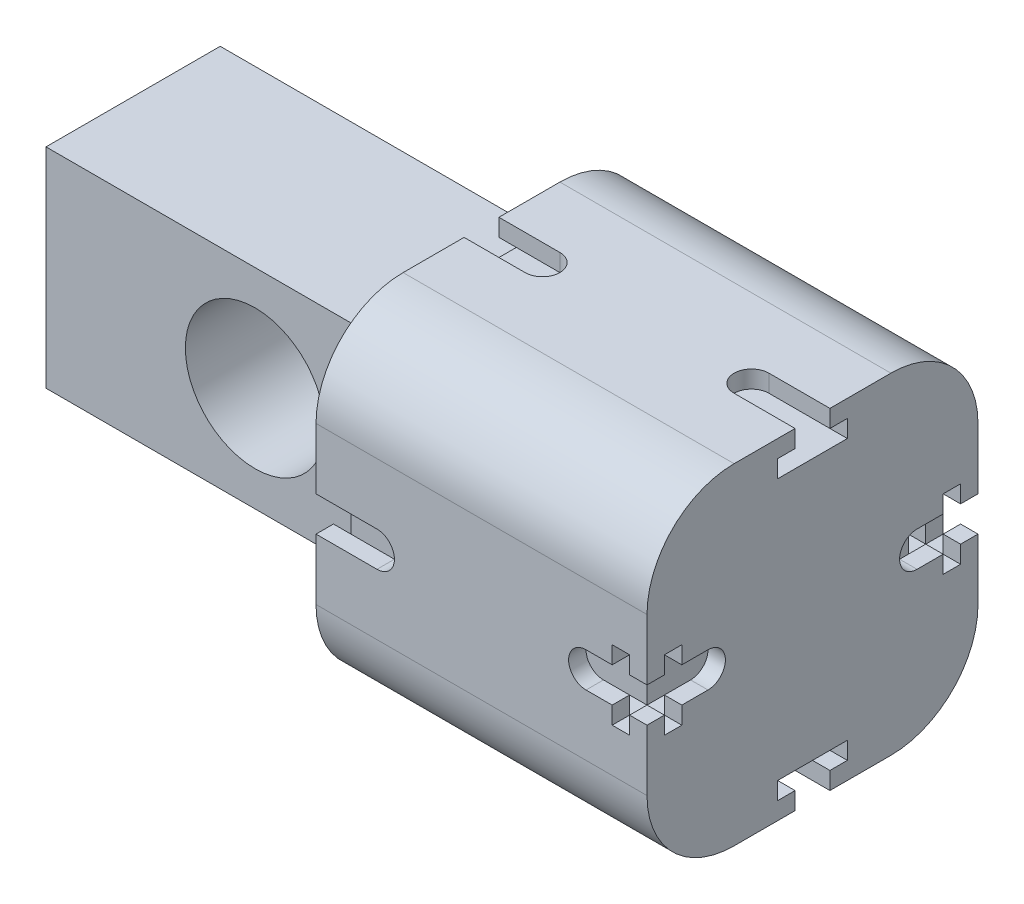
SolidWorks part; units mm, degrees
ref_plane "前视基准面" through (0, 0, 0) normal (0, 0, 1) x (1, 0, 0)
ref_plane "上视基准面" through (0, 0, 0) normal (0, 1, 0) x (1, 0, 0)
ref_plane "右视基准面" through (0, 0, 0) normal (1, 0, 0) x (0, 0, -1)
sketch "草图2" plane through (0, 0, 0) normal (0, 0, 1) x (1, 0, 0)
  line L1 (-9.5, 9.5) -> (9.5, 9.5)
  line L2 (-9.5, 9.5) -> (-9.5, -9.5)
  line L3 (-9.5, -9.5) -> (9.5, -9.5)
  line L4 (9.5, 9.5) -> (9.5, -9.5)
  line L5 (-9.5, 9.5) -> (9.5, -9.5) construction
  line L6 (-9.5, -9.5) -> (9.5, 9.5) construction
  point P0 (0, 0)
extrude "凸台-拉伸1" add sketch "草图2" along normal mid plane 19
fillet "圆角1" radius 5 1 edges at (0, 9.5, 9.5)
fillet "圆角2" radius 5 3 edges at (0, -9.5, 9.5) (0, 9.5, -9.5) (0, -9.5, -9.5)
ref_plane "基准面1" through (0, -7.5, 0) normal (0, -1, 0) x (-1, 0, 0)
sketch "草图7" plane through (0, -7.5, 0) normal (0, -1, 0) x (-1, 0, 0)
  line L0 (9.5, -4.5) -> (9.5, 4.5) construction
  line L1 (-9.5, 2) -> (-4, 2)
  line L2 (-9.5, 2) -> (-9.5, -2)
  line L3 (-9.5, -2) -> (-4, -2)
  line L4 (9.5, 2) -> (9.5, -2)
  line L5 (4, 2) -> (9.5, 2)
  line L6 (4, -2) -> (9.5, -2)
  line L9 (-4, 2) -> (-4, -2)
  line L11 (4, 2) -> (4, -2)
  point P0 (0, 0)
  point P8 (0, 0)
sketch "草图9" plane through (0, -9.5, 0) normal (0, -1, 0) x (1, 0, 0)
  line L0 (6, 1) -> (9.5, 1)
  line L1 (9.5, 1) -> (9.5, -1)
  line L2 (9.5, -1) -> (6, -1)
  line L4 (-9.5, 1) -> (-9.5, -1)
  line L5 (-6, 1) -> (-9.5, 1)
  line L6 (-9.5, -1) -> (-6, -1)
  arc A0 (6, 1) -> (6, -1) centre (6, 0) ccw
  arc A1 (-6, 1) -> (-6, -1) centre (-6, 0) cw
extrude "切除-拉伸5" cut sketch "草图7" along normal blind 1
extrude "切除-拉伸6" cut sketch "草图9" against normal blind 1
ref_plane "基准面2" through (0, 0, 7.5) normal (0, 0, 1) x (1, 0, 0)
ref_plane "基准面3" through (0, 7.5, 0) normal (0, 1, 0) x (1, 0, 0)
ref_plane "基准面4" through (0, 0, -7.5) normal (0, 0, -1) x (-1, 0, 0)
sketch "草图13" plane through (0, 0, 7.5) normal (0, 0, 1) x (1, 0, 0)
  line L1 (-9.5, 2) -> (-4, 2)
  line L2 (-9.5, 2) -> (-9.5, -2)
  line L3 (-9.5, -2) -> (-4, -2)
  line L4 (9.5, 2) -> (9.5, -2)
  line L5 (4, 2) -> (9.5, 2)
  line L6 (4, -2) -> (9.5, -2)
  line L9 (-4, 2) -> (-4, -2)
  line L11 (4, 2) -> (4, -2)
  point P0 (0, 0)
  point P8 (0, 0)
sketch "草图14" plane through (0, 7.5, 0) normal (0, 1, 0) x (1, 0, 0)
  line L1 (-9.5, 2) -> (-4, 2)
  line L2 (-9.5, 2) -> (-9.5, -2)
  line L3 (-9.5, -2) -> (-4, -2)
  line L4 (9.5, 2) -> (9.5, -2)
  line L5 (4, 2) -> (9.5, 2)
  line L6 (4, -2) -> (9.5, -2)
  line L9 (-4, 2) -> (-4, -2)
  line L11 (4, 2) -> (4, -2)
  point P0 (0, 0)
  point P8 (0, 0)
sketch "草图15" plane through (0, 0, -7.5) normal (0, 0, -1) x (-1, 0, 0)
  line L1 (-9.5, 2) -> (-4, 2)
  line L2 (-9.5, 2) -> (-9.5, -2)
  line L3 (-9.5, -2) -> (-4, -2)
  line L4 (9.5, 2) -> (9.5, -2)
  line L5 (4, 2) -> (9.5, 2)
  line L6 (4, -2) -> (9.5, -2)
  line L9 (-4, 2) -> (-4, -2)
  line L11 (4, 2) -> (4, -2)
  point P0 (0, 0)
  point P8 (0, 0)
extrude "切除-拉伸10" cut sketch "草图13" along normal blind 1
extrude "切除-拉伸11" cut sketch "草图14" along normal blind 1
extrude "切除-拉伸12" cut sketch "草图15" along normal blind 1
sketch "草图20" plane through (0, 0, 7.5) normal (0, 0, 1) x (-1, 0, 0)
  line L0 (6, 1) -> (9.5, 1)
  line L1 (9.5, 1) -> (9.5, -1)
  line L2 (9.5, -1) -> (6, -1)
  line L4 (-9.5, 1) -> (-9.5, -1)
  line L5 (-6, 1) -> (-9.5, 1)
  line L6 (-9.5, -1) -> (-6, -1)
  arc A0 (6, 1) -> (6, -1) centre (6, 0) ccw
  arc A1 (-6, 1) -> (-6, -1) centre (-6, 0) cw
sketch "草图21" plane through (0, 7.5, 0) normal (0, 1, 0) x (-1, 0, 0)
  line L0 (6, 1) -> (9.5, 1)
  line L1 (9.5, 1) -> (9.5, -1)
  line L2 (9.5, -1) -> (6, -1)
  line L4 (-9.5, 1) -> (-9.5, -1)
  line L5 (-6, 1) -> (-9.5, 1)
  line L6 (-9.5, -1) -> (-6, -1)
  arc A0 (6, 1) -> (6, -1) centre (6, 0) ccw
  arc A1 (-6, 1) -> (-6, -1) centre (-6, 0) cw
sketch "草图22" plane through (0, 0, -7.5) normal (0, 0, -1) x (1, 0, 0)
  line L0 (6, 1) -> (9.5, 1)
  line L1 (9.5, 1) -> (9.5, -1)
  line L2 (9.5, -1) -> (6, -1)
  line L4 (-9.5, 1) -> (-9.5, -1)
  line L5 (-6, 1) -> (-9.5, 1)
  line L6 (-9.5, -1) -> (-6, -1)
  arc A0 (6, 1) -> (6, -1) centre (6, 0) ccw
  arc A1 (-6, 1) -> (-6, -1) centre (-6, 0) cw
extrude "切除-拉伸13" cut sketch "草图20" along normal blind 2
extrude "切除-拉伸14" cut sketch "草图21" along normal blind 2
extrude "切除-拉伸15" cut sketch "草图22" along normal blind 2
ref_plane "基准面5" through (7.5, 0, 0) normal (1, 0, 0) x (0, 0, -1)
sketch "草图23" plane through (7.5, 0, 0) normal (1, 0, 0) x (0, 0, -1)
  line L1 (-9.5, 2) -> (-4, 2)
  line L2 (-9.5, 2) -> (-9.5, -2)
  line L3 (-9.5, -2) -> (-4, -2)
  line L4 (9.5, 2) -> (9.5, -2)
  line L5 (4, 2) -> (9.5, 2)
  line L6 (4, -2) -> (9.5, -2)
  line L9 (-4, 2) -> (-4, -2)
  line L11 (4, 2) -> (4, -2)
  point P0 (0, 0)
  point P8 (0, 0)
extrude "切除-拉伸16" cut sketch "草图23" along normal blind 1
sketch "草图24" plane through (7.5, 0, 0) normal (1, 0, 0) x (0, 0, 1)
  line L0 (6, 1) -> (9.5, 1)
  line L1 (9.5, 1) -> (9.5, -1)
  line L2 (9.5, -1) -> (6, -1)
  line L4 (-9.5, 1) -> (-9.5, -1)
  line L5 (-6, 1) -> (-9.5, 1)
  line L6 (-9.5, -1) -> (-6, -1)
  arc A0 (6, 1) -> (6, -1) centre (6, 0) ccw
  arc A1 (-6, 1) -> (-6, -1) centre (-6, 0) cw
extrude "切除-拉伸17" cut sketch "草图24" along normal blind 2
ref_plane "基准面6" through (-7.5, 0, 0) normal (-1, 0, 0) x (0, 0, 1)
sketch "草图27" plane through (-9.5, 0, 0) normal (-1, 0, 0) x (0, 0, 1)
  line L5 (-5, 6) -> (5, 6)
  line L6 (-5, 6) -> (-5, -6)
  line L7 (-5, -6) -> (5, -6)
  line L8 (5, 6) -> (5, -6)
  line L9 (-5, 6) -> (5, -6) construction
  line L10 (-5, -6) -> (5, 6) construction
  point P0 (0, 0)
  point P1 (0, 0)
  dimension "D1" = 12
  dimension "D2" = 10
extrude "凸台-拉伸2" add sketch "草图27" along normal blind 20
sketch "草图28" plane through (0, 0, 0) normal (0, 0, 1) x (1, 0, 0)
  line L0 (-9.5, 4.5) -> (-9.5, 1) construction
  circle A0 centre (-17.5, 0) radius 4
  dimension "D1" = 8
extrude "切除-拉伸20" cut sketch "草图28" against normal mid plane 20
sketch "草图11" plane through (0, 7.5, 0) normal (0, 1, 0) x (-1, 0, 0)
  line L0 (6, 1) -> (9.5, 1)
  line L1 (9.5, 1) -> (9.5, -1)
  line L2 (9.5, -1) -> (6, -1)
  line L4 (-9.5, 1) -> (-9.5, -1)
  line L5 (-6, 1) -> (-9.5, 1)
  line L6 (-9.5, -1) -> (-6, -1)
  arc A0 (6, 1) -> (6, -1) centre (6, 0) ccw
  arc A1 (-6, 1) -> (-6, -1) centre (-6, 0) cw
sketch "草图12" plane through (0, 0, -7.5) normal (0, 0, -1) x (1, 0, 0)
  line L0 (6, 1) -> (9.5, 1)
  line L1 (9.5, 1) -> (9.5, -1)
  line L2 (9.5, -1) -> (6, -1)
  line L4 (-9.5, 1) -> (-9.5, -1)
  line L5 (-6, 1) -> (-9.5, 1)
  line L6 (-9.5, -1) -> (-6, -1)
  arc A0 (6, 1) -> (6, -1) centre (6, 0) ccw
  arc A1 (-6, 1) -> (-6, -1) centre (-6, 0) cw
